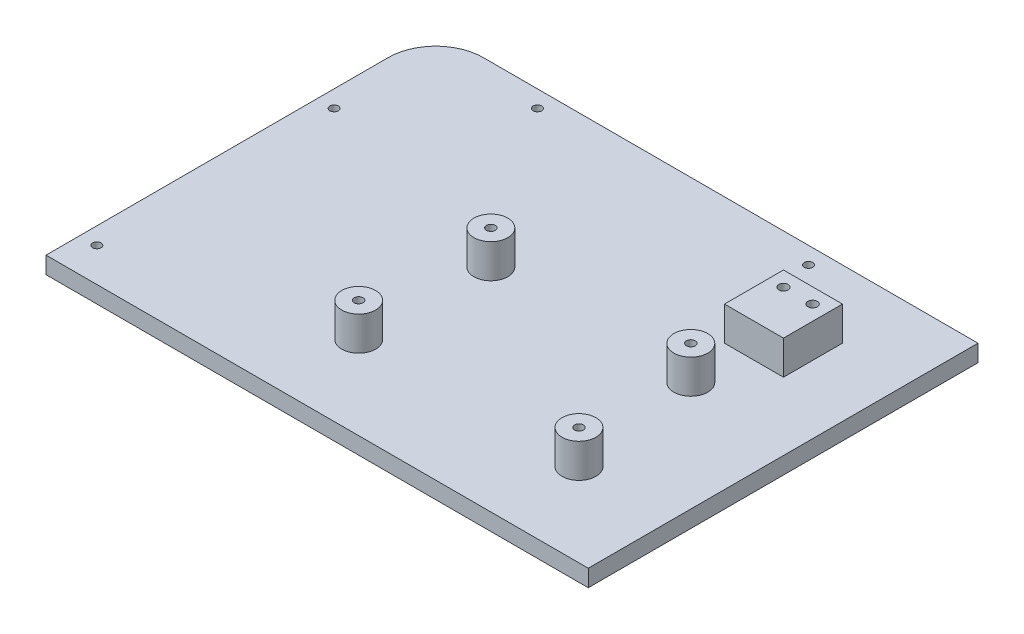
SolidWorks part; units mm, degrees
material "ABS"
ref_plane "Front Plane" through (0, 0, 0) normal (0, 0, 1) x (1, 0, 0)
ref_plane "Top Plane" through (0, 0, 0) normal (0, 1, 0) x (1, 0, 0)
ref_plane "Right Plane" through (0, 0, 0) normal (1, 0, 0) x (0, 0, -1)
sketch "Sketch1" plane through (0, 0, 0) normal (0, 1, 0) x (1, 0, 0)
  line L1 (0, 0) -> (203.2, 0)
  line L2 (0, 0) -> (0, 128.27)
  line L3 (17.78, 146.05) -> (203.2, 146.05)
  line L4 (203.2, 0) -> (203.2, 146.05)
  circle A0 centre (6.35, 12.7) radius 1.5875
  arc A1 (17.78, 146.05) -> (0, 128.27) centre (17.78, 128.27) ccw
  circle A2 centre (6.35, 101.6) radius 1.5875
  circle A3 centre (44.45, 139.7) radius 1.5875
  circle A4 centre (146.05, 139.7) radius 1.5875
  point P9 (0, 146.05)
  dimension "D3" = 17.78
  dimension "D4" = 3.175
  dimension "D1" = 146.05
  dimension "D2" = 203.2
  dimension "D5" = 6.35
  dimension "D6" = 12.7
  dimension "D7" = 88.9
  dimension "D8" = 6.35
  dimension "D9" = 57.15
  dimension "D10" = 101.6
extrude "Boss-Extrude1" add sketch "Sketch1" along normal blind 6.35
sketch "Sketch2" plane through (0, 6.35, 0) normal (0, 1, 0) x (1, 0, 0)
  line L1 (177.8, 120.65) -> (155.702, 120.65)
  line L2 (177.8, 120.65) -> (177.8, 98.552)
  line L3 (177.8, 98.552) -> (155.702, 98.552)
  line L4 (155.702, 120.65) -> (155.702, 98.552)
  line L5 (203.2, 146.05) -> (17.78, 146.05) construction
  line L6 (203.2, 0) -> (203.2, 146.05) construction
  circle A0 centre (172.212, 115.062) radius 1.778
  circle A1 centre (161.29, 115.062) radius 1.778
  dimension "D5" = 3.556
  dimension "D1" = 22.098
  dimension "D2" = 22.098
  dimension "D3" = 25.4
  dimension "D4" = 25.4
  dimension "D6" = 10.922
  dimension "D7" = 5.588
  dimension "D8" = 5.588
extrude "Boss-Extrude2" add sketch "Sketch2" along normal blind 12.7
sketch "Sketch3" plane through (0, 6.35, 0) normal (0, 1, 0) x (1, 0, 0)
  line L0 (155.702, 98.552) -> (177.8, 98.552) construction
  circle A0 centre (162.1337, 79.502) radius 6.35
  circle A1 centre (168.4837, 31.242) radius 6.35
  circle A2 centre (87.2037, 79.502) radius 6.35
  circle A3 centre (85.9337, 31.242) radius 6.35
  dimension "D1" = 12.7
  dimension "D2" = 19.05
  dimension "D3" = 48.26
  dimension "D4" = 1.27
  dimension "D5" = 74.93
  dimension "D6" = 82.55
extrude "Boss-Extrude3" add sketch "Sketch3" along normal blind 12.7 contours A0 | A1 | A3 | A2
sketch "Sketch5" plane through (0, 19.05, 0) normal (0, 1, 0) x (1, 0, 0)
  circle A0 centre (168.4837, 31.242) radius 1.651
  circle A1 centre (162.1337, 79.502) radius 1.651
  circle A2 centre (87.2037, 79.502) radius 1.651
  circle A3 centre (85.9337, 31.242) radius 1.651
  dimension "D1" = 3.302
extrude "Cut-Extrude1" cut sketch "Sketch5" against normal through all
